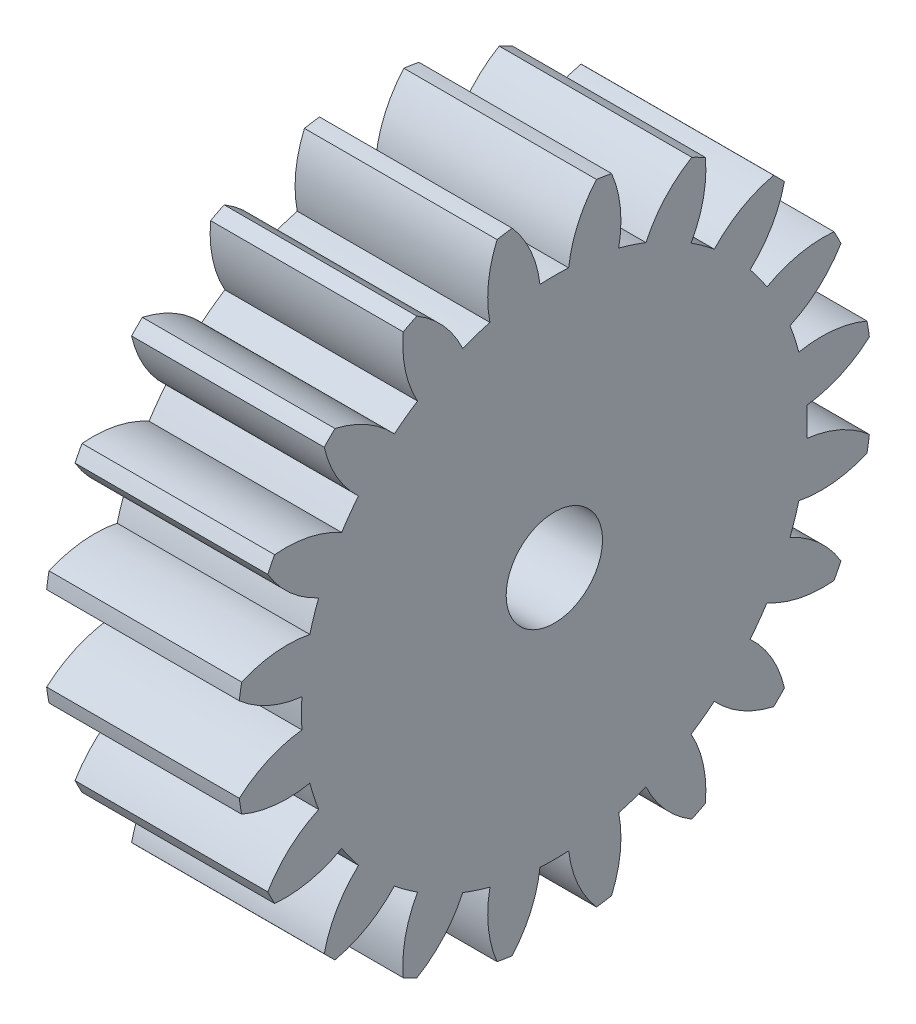
SolidWorks part; units mm, degrees
ref_plane "Plane1" through (0, 0, 0) normal (0, 0, 1) x (1, 0, 0)
ref_plane "Plane2" through (0, 0, 0) normal (0, 1, 0) x (1, 0, 0)
ref_plane "Plane3" through (0, 0, 0) normal (1, 0, 0) x (0, 0, -1)
other "Configuration Table"
sketch "HoldingSke" plane through (0, 0, 0) normal (0, 1, 0) x (1, 0, 0)
  line L0 (0, 0) -> (0.6265, -0.228)
  line L1 (-15, 0) -> (100, 0) construction
  line L2 (0, 0) -> (-2.1039, 2.3779)
  line L3 (0, 0) -> (-11.863, 4.5341)
  line L4 (0, 0) -> (8.1152, 2.9537)
  line L5 (0, 0) -> (-46.8476, -17.4728)
  line L6 (0, 0) -> (-8.2896, -5.593)
  line L7 (-2.1039, 2.3779) -> (8.6586, 51.2059)
  line L8 (-76.2, 54.61) -> (-75.3, 54.61)
  line L9 (-71.009, 38.7566) -> (-53.1078, 45.2721)
  line L10 (-76.2, 71.12) -> (104.1128, 71.12)
  line L11 (0, 0) -> (-10, 0)
  line L12 (-76.2, 101.6) -> (-76.147, 101.6)
  line L13 (24.9733, 27.94) -> (52.9518, 28.4284)
  line L14 (24.9733, 27.94) -> (24.9743, 27.94)
  line L15 (24.9733, 27.94) -> (100.4006, 29.5858)
  line L16 (-63.627, -1.5) -> (-12.827, -1.5)
  circle A0 centre (0, 0) radius 2.5
  circle A1 centre (0, 0) radius 13.124
  circle A2 centre (0, 0) radius 37.5
  circle A3 centre (0, 0) radius 2.5
  dimension "MHD" = 26.248
  dimension "Hub_dia" = 75
  dimension "Bore" = 5
  dimension "MBD" = 5
  dimension "Num_teeth" = 20
  dimension "Pitch" = 0.6667
  dimension "Overall_len" = 50
  dimension "Show_teeth" = 20
  dimension "OAL" = 50.0001
  dimension "T_dim" = 0.9
  dimension "Ap" = 20
  dimension "H" = 19.05
  dimension "Pitch_radius" = 180.3128
  dimension "Backlash" = 0.053
  dimension "Addendum_fac" = 1
  dimension "Dedendum_fac" = 1.25
  dimension "Clearance_fac" = 0.25
  dimension "Dedendum_add" = 0.001
  dimension "Module" = 1.5
sketch "BasProSke" plane through (0, 0, 0) normal (0, 1, 0) x (1, 0, 0)
  line L0 (-10, 0) -> (60, 0) construction
  line L1 (0, 0) -> (0, 16.5)
  line L2 (0, 0) -> (10, 0)
  line L3 (10, 0) -> (10, 16.5)
  line L4 (10, 16.5) -> (0, 16.5)
  dimension "Diameter" = 33
revolve "Base-Revolve" add sketch "BasProSke" angle 360 about L0
sketch "TooCutSke" plane through (0, 0, 0) normal (1, 0, 0) x (0, 0, -1)
  line L1 (0, 0) -> (0, 107) construction
  line L2 (0, 0) -> (-1.2696, 14.9462) construction
  line L3 (0, 0) -> (-4.6808, 29.5532) construction
  line L4 (-1.2696, 14.9462) -> (-2.3404, 14.7766) construction
  arc A0 (0.7438, 13.1029) -> (-0.7438, 13.1029) centre (0, 0) ccw
  arc A1 (2.21, 16.377) -> (-2.21, 16.377) centre (0, 0) ccw
  circle A2 centre (0, 0) radius 15 construction
  circle A3 centre (0, 0) radius 14.0954 construction
  arc A4 (-0.7438, 13.1029) -> (-2.21, 16.377) centre (-6.7025, 12.3999) ccw
  arc A5 (2.21, 16.377) -> (0.7438, 13.1029) centre (6.7025, 12.3999) ccw
  dimension "Root_dia" = 26.248
  dimension "Overcut_dia" = 33.0508
  dimension "Pitch_dia" = 30
  dimension "Base_dia" = 28.1908
  dimension "Flank_rad" = 6
  dimension "Half_ang" = 9
  dimension "Half_CT" = 1.0841
extrude "ToothCut" cut sketch "TooCutSke" along normal through all
fillet "Breaks" [suppressed] radius 0.03
fillet "RootFillets" [suppressed] radius 0.376
pattern_circular "TeethCuts" count 20 every 18 about axis through (-10, 0, 0) along (1, 0, 0) of "ToothCut", "RootFillets", "Breaks"
sketch "HubNeaOneSke" plane through (0, 0, 0) normal (-1, 0, 0) x (0, 0, 1)
  circle A0 centre (0, 0) radius 13.124
  dimension "Diameter" = 26.248
extrude "HubNearOne" [suppressed] add sketch "HubNeaOneSke" along normal blind 40.0001
sketch "HubNeaBotSke" plane through (0, 0, 0) normal (-1, 0, 0) x (0, 0, 1)
  circle A0 centre (0, 0) radius 13.124
  dimension "Diameter" = 26.248
extrude "HubNearBoth" [suppressed] add sketch "HubNeaBotSke" along normal blind 20
ref_plane "FarPln" through (10, 0, 0) normal (1, 0, 0) x (0, 0, -1)
sketch "HubFarSke" plane through (10, 0, 0) normal (1, 0, 0) x (0, 0, -1)
  circle A0 centre (0, 0) radius 13.124
  dimension "Diameter" = 26.248
extrude "HubFar" [suppressed] add sketch "HubFarSke" along normal blind 20
sketch "BorSke" plane through (0, 0, 0) normal (1, 0, 0) x (0, 0, -1)
  circle A0 centre (0, 0) radius 2.5
  dimension "Diameter" = 5
extrude "Bore" cut sketch "BorSke" along normal mid plane 100.0001
sketch "KeySke" plane through (0, 0, 0) normal (1, 0, 0) x (0, 0, -1)
  line L0 (-1, 0) -> (-1, 3.4)
  line L1 (-1, 3.4) -> (1, 3.4)
  line L2 (1, 3.4) -> (1, 0)
  line L3 (0, 0) -> (0, 34) construction
  line L4 (-1, 0) -> (1, 0)
  dimension "Offset" = 3.4
  dimension "Width" = 2
extrude "Keyway" [suppressed] cut sketch "KeySke" along normal mid plane 100.0001
pattern_circular "Keyway2" [suppressed] count 2 every 90 about axis through (-10, 0, 0) along (1, 0, 0)
equation "' \"Module@HoldingSke\" = 6.35"
equation "' \"Num_teeth@HoldingSke\" = 12"
equation "' \"Ap@HoldingSke\" =  20"
equation "' \"Ap@HoldingSke\" = 20"
equation "' \"Width@HoldingSke\" = 0.5 * 25.4"
equation "' \"Hub_dia@HoldingSke\"= 1 * 25.4"
equation "' \"Hub_dia@HoldingSke\" = 1 * 25.4"
equation "' \"Overall_len@HoldingSke\" = 1.0 * 25.4"
equation "' \"Bore@HoldingSke\" = 0.75 * 25.4"
equation "' \"T_dim@HoldingSke\" = 0.1 * 25.4"
equation "' \"Width@KeySke\" = 0.25 * 25.4"
equation "' \"Show_teeth@HoldingSke\" = 13"
equation "' \"Backlash@HoldingSke\" = 0.009 * 25.4"
equation "' \"Addendum_fac@HoldingSke\" = 1.0"
equation "' \"Dedendum_fac@HoldingSke\" = 1.25"
equation "' \"Dedendum_add@HoldingSke\" = 0.00005 * 25.4"
equation "' \"Clearance_fac@HoldingSke\" = 0.25"
equation "\"Pitch@HoldingSke\" = 1 / \"Module@HoldingSke\""
equation "\"Overcut_dia@TooCutSke\" = (\"Num_teeth@HoldingSke\" + 2 * \"Addendum_fac@HoldingSke\") / \"Pitch@HoldingSke\" + 0.002 * 25.4"
equation "\"Pitch_dia@TooCutSke\" = \"Num_teeth@HoldingSke\" / \"Pitch@HoldingSke\""
equation "\"Base_dia@TooCutSke\" = \"Num_teeth@HoldingSke\" / \"Pitch@HoldingSke\" * cos((\"Ap@HoldingSke\"  * 3.14159265 / 180))"
equation "\"Root_dia@TooCutSke\" = (\"Num_teeth@HoldingSke\" + 2) / \"Pitch@HoldingSke\" - 2 * (\"Addendum_fac@HoldingSke\" + \"Dedendum_fac@HoldingSke\") / \"Pitch@HoldingSke\" - \"Dedendum_add@HoldingSke\" * 2"
equation "\"Half_ang@TooCutSke\" = 180 / \"Num_teeth@HoldingSke\""
equation "\"Half_CT@TooCutSke\" = \"Num_teeth@HoldingSke\" / \"Pitch@HoldingSke\" * sin((3.14159265 / 2 / \"Num_teeth@HoldingSke\")) / 2 - 7 * \"Backlash@HoldingSke\" / 4"
equation "\"Flank_rad@TooCutSke\" = \"Num_teeth@HoldingSke\" / \"Pitch@HoldingSke\" / 5"
equation "\"Radius@RootFillets\" = \"Clearance_fac@HoldingSke\" / \"Pitch@HoldingSke\" + \"Dedendum_add@HoldingSke\""
equation "\"Break_rad@Breaks\" = 0.02 / \"Pitch@HoldingSke\""
equation "\"Thickness@HoldingSke\" = \"Width@HoldingSke\""
equation "\"OAL@HoldingSke\" = \"Thickness@HoldingSke\""
equation "\"MHD@HoldingSke\" = (\"Num_teeth@HoldingSke\" + 2) / \"Pitch@HoldingSke\" - 2 * (\"Addendum_fac@HoldingSke\" + \"Dedendum_fac@HoldingSke\")  / \"Pitch@HoldingSke\" - \"Dedendum_add@HoldingSke\" * 2"
equation "\"MBD@HoldingSke\" = (\"Num_teeth@HoldingSke\" + 2) / \"Pitch@HoldingSke\" - 2 * (\"Addendum_fac@HoldingSke\" + \"Dedendum_fac@HoldingSke\")  / \"Pitch@HoldingSke\" - \"Dedendum_add@HoldingSke\" * 2 - 0.002 * 25.4"
equation "\"MHD@HoldingSke\" = ((sgn( \"MHD@HoldingSke\" - \"Hub_dia@HoldingSke\" )-1)*( \"MHD@HoldingSke\" - \"Hub_dia@HoldingSke\" ))/-2+ \"Hub_dia@HoldingSke\""
equation "\"MBD@HoldingSke\" = ((sgn( \"MBD@HoldingSke\" - \"Bore@HoldingSke\" )-1)*( \"MBD@HoldingSke\" - \"Bore@HoldingSke\" ))/-2+ \"Bore@HoldingSke\""
equation "\"OAL@HoldingSke\" = ((sgn( \"OAL@HoldingSke\" - \"Overall_len@HoldingSke\" )+1)*( \"OAL@HoldingSke\" - \"Overall_len@HoldingSke\" ))/2 + \"Overall_len@HoldingSke\" + 0.000002 * 25.4"
equation "\"Num_teeth@TeethCuts\" = int( \"Show_teeth@HoldingSke\" ) + 1"
equation "\"Num_teeth@TeethCuts\" = ((sgn( \"Num_teeth@TeethCuts\" - \"Num_teeth@HoldingSke\" )-1)*( \"Num_teeth@TeethCuts\" - \"Num_teeth@HoldingSke\" ))/-2+ \"Num_teeth@HoldingSke\""
equation "\"Num_teeth@TeethCuts\" = ((sgn( \"Num_teeth@TeethCuts\" - 2.0)+1)*( \"Num_teeth@TeethCuts\" - 2.0))/2 +2.0"
equation "\"Angle@TeethCuts\" = 360.0 / \"Num_teeth@HoldingSke\""
equation "\"Diameter@BasProSke\" = (\"Num_teeth@HoldingSke\" + 2 * \"Addendum_fac@HoldingSke\") / \"Pitch@HoldingSke\""
equation "\"Thickness@BasProSke\"  = \"Thickness@HoldingSke\""
equation "' \"Fillet_rad@BasProSke\" =  \"Thickness@HoldingSke\" * 0.05"
equation "' \"Fillet_rad@BasProSke\" = \"Thickness@HoldingSke\" * 0.05"
equation "\"MHD@HoldingSke\" = ((sgn( \"MHD@HoldingSke\" - \"Root_dia@TooCutSke\" )-1)*( \"MHD@HoldingSke\" - \"Root_dia@TooCutSke\" ))/-2+ \"Root_dia@TooCutSke\""
equation "\"Diameter@HubNeaOneSke\" = \"MHD@HoldingSke\""
equation "\"Length@HubNearOne\" = \"OAL@HoldingSke\" - \"Thickness@BasProSke\""
equation "\"Diameter@HubNeaBotSke\" = \"MHD@HoldingSke\""
equation "\"Length@HubNearBoth\" = ( \"OAL@HoldingSke\" - \"Thickness@BasProSke\" ) / 2.0"
equation "\"Thickness@FarPln\" = \"Thickness@BasProSke\""
equation "\"Diameter@HubFarSke\" = \"MHD@HoldingSke\""
equation "\"Length@HubFar\" = ( \"OAL@HoldingSke\" - \"Thickness@BasProSke\" ) / 2.0"
equation "\"Diameter@BorSke\" = \"MBD@HoldingSke\""
equation "\"D1@Bore\" = \"OAL@HoldingSke\" * 2.0"
equation "\"D1@Keyway\" = \"OAL@HoldingSke\" * 2.0"
equation "\"Offset@KeySke\" = \"T_dim@HoldingSke\" + \"MBD@HoldingSke\" / 2.0"
